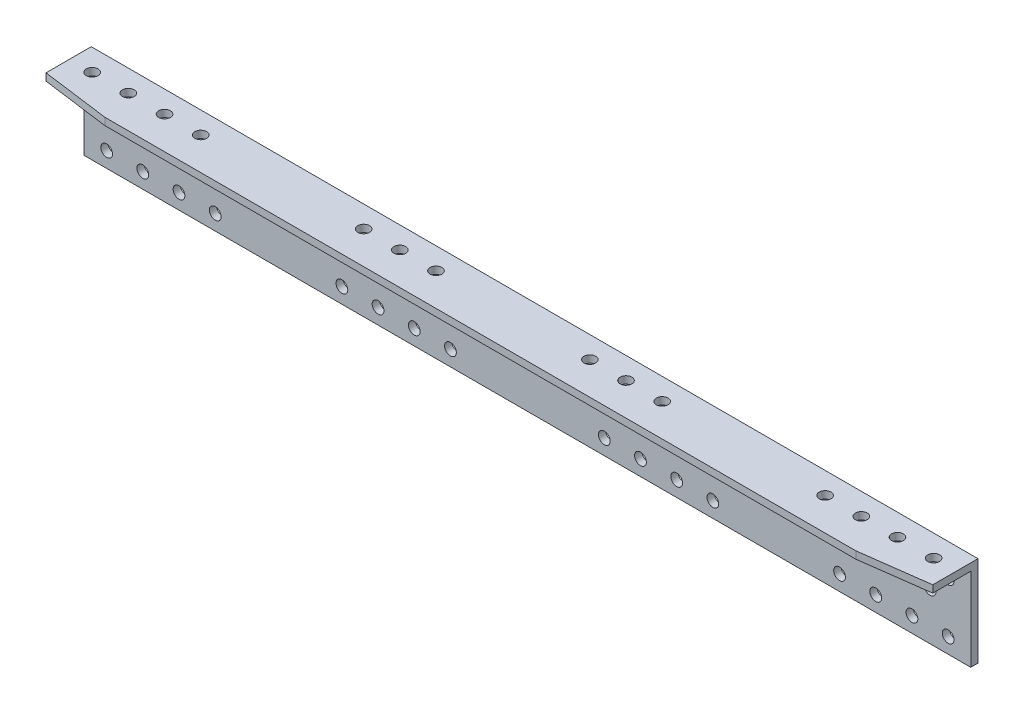
SolidWorks part; units mm, degrees
material "PW90:Mi:0:31:Ar:0:-1:Sc:1:So:2:Re:16:Ts:17:18:19:20:21:22:"
ref_plane "前视" through (0, 0, 0) normal (0, 0, 1) x (1, 0, 0)
ref_plane "上视" through (0, 0, 0) normal (0, 1, 0) x (1, 0, 0)
ref_plane "右视" through (0, 0, 0) normal (1, 0, 0) x (0, 0, -1)
sketch "草图1" plane through (0, 0, 0) normal (0, 0, 1) x (1, 0, 0)
  line L0 (0, 0) -> (0, 200.0571) construction
  line L1 (0, 200.0571) -> (0, 106) construction
  line L2 (210, 146) -> (953.1711, 146) construction
  line L3 (-980, 200) -> (980, 200)
  line L4 (-980, 200) -> (-980, 0)
  line L5 (-980, 0) -> (980, 0)
  line L6 (980, 200) -> (980, 0)
  line L7 (143, 106) -> (308.6181, 106) construction
  line L8 (930, 159) -> (930, 17.8164) construction
  line L9 (953.1711, 34) -> (210, 34) construction
  line L10 (890, 175.3513) -> (890, 17.8164) construction
  line L11 (850, 159) -> (850, 17.8164) construction
  line L12 (810, 175.3513) -> (810, 17.8164) construction
  line L13 (770, 175.3513) -> (770, 17.8164) construction
  line L14 (730, 175.3513) -> (730, 17.8164) construction
  line L15 (0, 0) -> (330, 0) construction
  line L16 (0, 0) -> (1632.9772, 0) construction
  line L17 (-1004.6224, 106) -> (1007.8631, 106) construction
  line L18 (650, 175.3513) -> (650, 17.8164) construction
  line L19 (690, 175.3513) -> (690, 17.8164) construction
  line L20 (550, 175.3513) -> (550, 17.8164) construction
  line L21 (450, 293.2849) -> (450, -102.0826) construction
  line L22 (370, 293.2849) -> (370, -134.4898) construction
  line L23 (290, 293.2849) -> (290, -79.3976) construction
  line L24 (210, 293.2849) -> (210, -79.3976) construction
  line L25 (130, 293.2849) -> (130, -79.3976) construction
  line L26 (410, 320.2436) -> (410, -207.8775) construction
  circle A0 centre (930, 146) radius 13
  circle A1 centre (-890, 106) radius 13
  circle A2 centre (850, 146) radius 13
  circle A3 centre (930, 34) radius 13
  circle A4 centre (850, 34) radius 13
  circle A5 centre (-810, 106) radius 13
  circle A6 centre (770, 34) radius 13
  circle A7 centre (770, 146) radius 13
  circle A8 centre (-730, 106) radius 13
  circle A9 centre (690, 146) radius 13
  circle A10 centre (690, 34) radius 13
  circle A11 centre (-650, 106) radius 13
  circle A12 centre (170, 146) radius 13
  circle A13 centre (170, 34) radius 13
  circle A14 centre (-410, 146) radius 13
  circle A15 centre (250, 34) radius 13
  circle A16 centre (250, 146) radius 13
  circle A17 centre (-450, 106) radius 13
  circle A18 centre (330, 34) radius 13
  circle A19 centre (330, 146) radius 13
  circle A20 centre (-370, 106) radius 13
  circle A21 centre (-290, 106) radius 13
  circle A22 centre (-210, 106) radius 13
  circle A23 centre (890, 106) radius 13
  circle A24 centre (810, 106) radius 13
  circle A25 centre (650, 106) radius 13
  circle A26 centre (730, 106) radius 13
  circle A27 centre (-330, 146) radius 13
  circle A28 centre (-330, 34) radius 13
  circle A29 centre (410, 146) radius 13
  circle A30 centre (-250, 146) radius 13
  circle A31 centre (-250, 34) radius 13
  circle A32 centre (450, 106) radius 13
  circle A33 centre (-170, 34) radius 13
  circle A34 centre (-170, 146) radius 13
  circle A35 centre (370, 106) radius 13
  circle A36 centre (-690, 146) radius 13
  circle A37 centre (290, 106) radius 13
  circle A38 centre (-770, 146) radius 13
  circle A39 centre (210, 106) radius 13
  circle A40 centre (-850, 146) radius 13
  circle A41 centre (130, 106) radius 13
  circle A42 centre (-930, 146) radius 13
  circle A43 centre (-690, 34) radius 13
  circle A44 centre (-770, 34) radius 13
  circle A45 centre (-850, 34) radius 13
  circle A46 centre (-930, 34) radius 13
  circle A47 centre (-130, 106) radius 13
  circle A48 centre (410, 34) radius 13
  circle A49 centre (-410, 34) radius 13
  dimension "D12" = 26
  dimension "D16" = 26
  dimension "D18" = 26
  dimension "D25" = 26
  dimension "D1" = 200
  dimension "D2" = 1960
  dimension "D3" = 54
  dimension "D4" = 40
  dimension "D5" = 72
  dimension "D6" = 50
  dimension "D7" = 40
  dimension "D8" = 80
  dimension "D9" = 80
  dimension "D10" = 80
  dimension "D11" = 80
  dimension "D13" = 80
  dimension "D14" = 80
  dimension "D15" = 100
  dimension "D19" = 530
  dimension "D20" = 80
  dimension "D21" = 80
  dimension "D22" = 80
  dimension "D23" = 80
  dimension "D24" = 40
extrude "基体-拉伸" add sketch "草图1" along normal blind 16
sketch "草图2" plane through (0, 0, 16) normal (0, 0, 1) x (1, 0, 0)
  line L0 (0, 0) -> (0, 345.2694) construction
  line L1 (980, 0) -> (980, 200) construction
  line L2 (-980, 200) -> (980, 200)
  line L3 (-980, 200) -> (-980, 184)
  line L4 (-980, 184) -> (980, 184)
  line L5 (980, 200) -> (980, 184)
  dimension "D1" = 16
extrude "凸台-拉伸1" add sketch "草图2" along normal blind 104
sketch "草图3" plane through (0, 200, 0) normal (0, 1, 0) x (-1, 0, 0)
  line L0 (-277.803, 48) -> (-964.3408, 48) construction
  line L1 (-980, 120) -> (980, 120) construction
  line L2 (-980, 120) -> (-980, 0) construction
  line L3 (-980, 100) -> (-830, 120)
  line L4 (-277.803, 48) -> (7.9594, 48) construction
  line L5 (0, 0) -> (0, 96) construction
  line L6 (980, 100) -> (830, 120)
  line L7 (-830, 120) -> (-980, 120)
  line L8 (-980, 120) -> (-980, 100)
  line L9 (830, 120) -> (980, 120)
  line L11 (980, 120) -> (980, 100)
  circle A0 centre (-930, 48) radius 13
  circle A1 centre (-850, 48) radius 13
  circle A2 centre (-770, 48) radius 13
  circle A3 centre (-690, 48) radius 13
  circle A4 centre (-330, 48) radius 13
  circle A5 centre (-250, 48) radius 13
  circle A6 centre (-170, 48) radius 13
  circle A7 centre (170, 48) radius 13
  circle A8 centre (250, 48) radius 13
  circle A9 centre (330, 48) radius 13
  circle A10 centre (930, 48) radius 13
  circle A11 centre (850, 48) radius 13
  circle A12 centre (770, 48) radius 13
  circle A13 centre (690, 48) radius 13
  point P4 (-830, 120)
  point P5 (-980, 100)
  dimension "D5" = 26
  dimension "D1" = 72
  dimension "D2" = 150
  dimension "D3" = 20
  dimension "D4" = 50
  dimension "D6" = 80
  dimension "D7" = 80
  dimension "D8" = 80
  dimension "D9" = 360
  dimension "D10" = 80
  dimension "D11" = 80
extrude "切除-拉伸1" cut sketch "草图3" against normal through all
